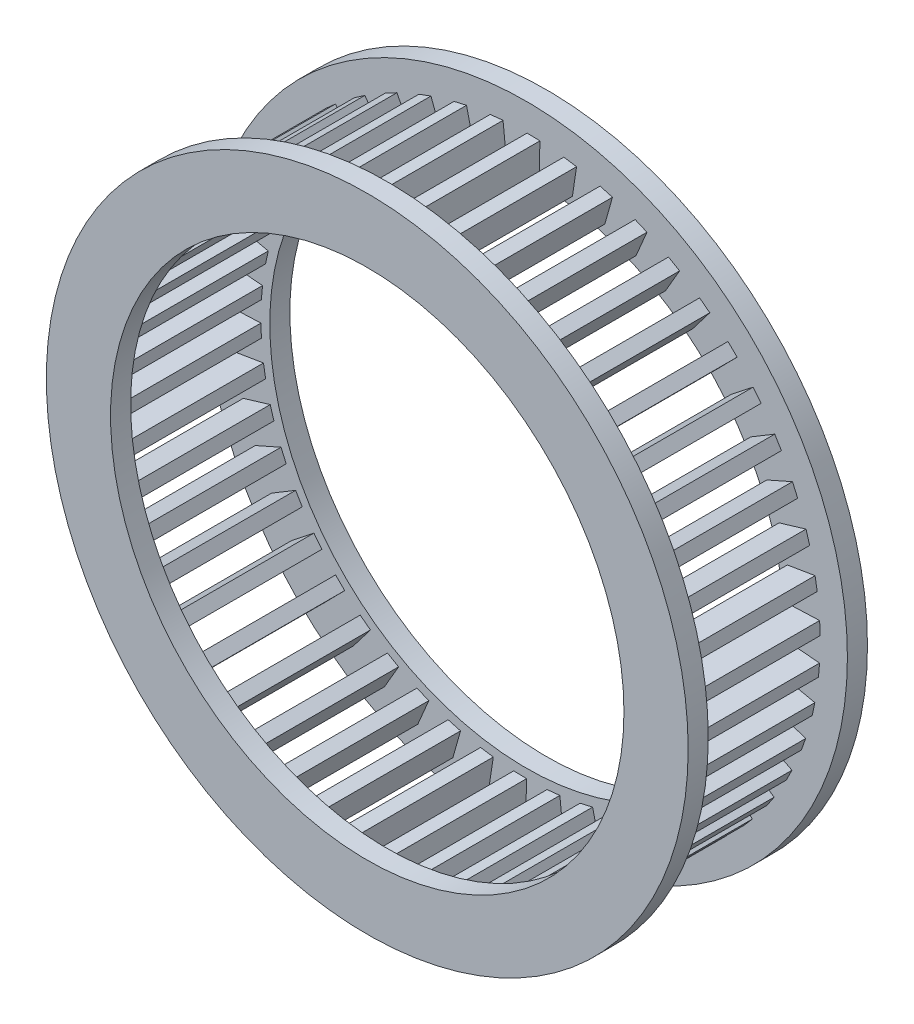
SolidWorks part; units mm, degrees
ref_plane "Спереди" through (0, 0, 0) normal (0, 0, 1) x (1, 0, 0)
ref_plane "Сверху" through (0, 0, 0) normal (0, 1, 0) x (1, 0, 0)
ref_plane "Справа" through (0, 0, 0) normal (1, 0, 0) x (0, 0, -1)
sketch "Эскиз1" plane through (0, 0, 0) normal (0, 0, 1) x (1, 0, 0)
  line L0 (76.3371, 1.1277) -> (84.4079, 1.4423)
  line L1 (84.4079, 1.4423) -> (84.2641, 5.1318)
  line L2 (84.2641, 5.1318) -> (76.1933, 4.8172)
  line L3 (76.1933, 4.8172) -> (76.3371, 1.1277)
  line L4 (75.5938, 10.6864) -> (83.5615, 12.01)
  line L5 (83.5615, 12.01) -> (82.9564, 15.6524)
  line L6 (82.9564, 15.6524) -> (74.9887, 14.3288)
  line L7 (74.9887, 14.3288) -> (75.5938, 10.6864)
  line L8 (73.6584, 20.0765) -> (81.3974, 22.3884)
  line L9 (81.3974, 22.3884) -> (80.3405, 25.9262)
  line L10 (80.3405, 25.9262) -> (72.6015, 23.6144)
  line L11 (72.6015, 23.6144) -> (73.6584, 20.0765)
  line L12 (70.5613, 29.1501) -> (77.9495, 32.4136)
  line L13 (77.9495, 32.4136) -> (76.4576, 35.7911)
  line L14 (76.4576, 35.7911) -> (69.0694, 32.5276)
  line L15 (69.0694, 32.5276) -> (70.5613, 29.1501)
  line L16 (66.3514, 37.7639) -> (73.2724, 41.9277)
  line L17 (73.2724, 41.9277) -> (71.3689, 45.0915)
  line L18 (71.3689, 45.0915) -> (64.448, 40.9278)
  line L19 (64.448, 40.9278) -> (66.3514, 37.7639)
  line L20 (61.0951, 45.7821) -> (67.4396, 50.7805)
  line L21 (67.4396, 50.7805) -> (65.1547, 53.6809)
  line L22 (65.1547, 53.6809) -> (58.8102, 48.6825)
  line L23 (58.8102, 48.6825) -> (61.0951, 45.7821)
  line L24 (54.8754, 53.0784) -> (60.5434, 58.8325)
  line L25 (60.5434, 58.8325) -> (57.9129, 61.4236)
  line L26 (57.9129, 61.4236) -> (52.2449, 55.6695)
  line L27 (52.2449, 55.6695) -> (54.8754, 53.0784)
  line L28 (47.7902, 59.5376) -> (52.6923, 65.9567)
  line L29 (52.6923, 65.9567) -> (49.7578, 68.1977)
  line L30 (49.7578, 68.1977) -> (44.8557, 61.7785)
  line L31 (44.8557, 61.7785) -> (47.7902, 59.5376)
  line L32 (39.9513, 65.0578) -> (44.0102, 72.0407)
  line L33 (44.0102, 72.0407) -> (40.818, 73.8963)
  line L34 (40.818, 73.8963) -> (36.7591, 66.9133)
  line L35 (36.7591, 66.9133) -> (39.9513, 65.0578)
  line L36 (31.4824, 69.552) -> (34.6341, 76.9886)
  line L37 (34.6341, 76.9886) -> (31.2345, 78.4294)
  line L38 (31.2345, 78.4294) -> (28.0828, 70.9928)
  line L39 (28.0828, 70.9928) -> (31.4824, 69.552)
  line L40 (22.5169, 72.9494) -> (24.7118, 80.7223)
  line L41 (24.7118, 80.7223) -> (21.1584, 81.7257)
  line L42 (21.1584, 81.7257) -> (18.9636, 73.9527)
  line L43 (18.9636, 73.9527) -> (22.5169, 72.9494)
  line L44 (13.1964, 75.1962) -> (14.3997, 83.183)
  line L45 (14.3997, 83.183) -> (10.7486, 83.7331)
  line L46 (10.7486, 83.7331) -> (9.5453, 75.7463)
  line L47 (9.5453, 75.7463) -> (13.1964, 75.1962)
  line L48 (3.6678, 76.2572) -> (3.8606, 84.3319)
  line L49 (3.8606, 84.3319) -> (0.1693, 84.42)
  line L50 (0.1693, 84.42) -> (-0.0235, 76.3454)
  line L51 (-0.0235, 76.3454) -> (3.6678, 76.2572)
  line L52 (-5.9187, 76.1156) -> (-6.7394, 84.1507)
  line L53 (-6.7394, 84.1507) -> (-10.4126, 83.7756)
  line L54 (-10.4126, 83.7756) -> (-9.5919, 75.7404)
  line L55 (-9.5919, 75.7404) -> (-5.9187, 76.1156)
  line L56 (-15.4119, 74.7736) -> (-17.2332, 82.6425)
  line L57 (-17.2332, 82.6425) -> (-20.8304, 81.8099)
  line L58 (-20.8304, 81.8099) -> (-19.0091, 73.941)
  line L59 (-19.0091, 73.941) -> (-15.4119, 74.7736)
  line L60 (-24.662, 72.2524) -> (-27.4552, 79.831)
  line L61 (-27.4552, 79.831) -> (-30.9196, 78.5541)
  line L62 (-30.9196, 78.5541) -> (-28.1265, 70.9755)
  line L63 (-28.1265, 70.9755) -> (-24.662, 72.2524)
  line L64 (-33.5231, 68.5917) -> (-37.2441, 75.7604)
  line L65 (-37.2441, 75.7604) -> (-40.5213, 74.0594)
  line L66 (-40.5213, 74.0594) -> (-36.8003, 66.8907)
  line L67 (-36.8003, 66.8907) -> (-33.5231, 68.5917)
  line L68 (-41.8556, 63.8493) -> (-46.4458, 70.4951)
  line L69 (-46.4458, 70.4951) -> (-49.4839, 68.3968)
  line L70 (-49.4839, 68.3968) -> (-44.8937, 61.7509)
  line L71 (-44.8937, 61.7509) -> (-41.8556, 63.8493)
  line L72 (-49.528, 58.0999) -> (-54.9149, 64.118)
  line L73 (-54.9149, 64.118) -> (-57.666, 61.6555)
  line L74 (-57.666, 61.6555) -> (-52.2792, 55.6373)
  line L75 (-52.2792, 55.6373) -> (-49.528, 58.0999)
  line L76 (-56.4193, 51.4343) -> (-62.518, 56.7298)
  line L77 (-62.518, 56.7298) -> (-64.9388, 53.9418)
  line L78 (-64.9388, 53.9418) -> (-58.8401, 48.6463)
  line L79 (-58.8401, 48.6463) -> (-56.4193, 51.4343)
  line L80 (-62.4208, 43.9575) -> (-69.1352, 48.4469)
  line L81 (-69.1352, 48.4469) -> (-71.1875, 45.3775)
  line L82 (-71.1875, 45.3775) -> (-64.4731, 40.8881)
  line L83 (-64.4731, 40.8881) -> (-62.4208, 43.9575)
  line L84 (-67.438, 35.7874) -> (-74.662, 39.3999)
  line L85 (-74.662, 39.3999) -> (-76.3134, 36.0975)
  line L86 (-76.3134, 36.0975) -> (-69.0894, 32.485)
  line L87 (-69.0894, 32.485) -> (-67.438, 35.7874)
  line L88 (-71.3916, 27.053) -> (-79.0114, 29.7316)
  line L89 (-79.0114, 29.7316) -> (-80.2359, 26.2483)
  line L90 (-80.2359, 26.2483) -> (-72.6161, 23.5697)
  line L91 (-72.6161, 23.5697) -> (-71.3916, 27.053)
  line L92 (-74.2193, 17.892) -> (-82.1147, 19.5944)
  line L93 (-82.1147, 19.5944) -> (-82.893, 15.9851)
  line L94 (-82.893, 15.9851) -> (-74.9975, 14.2826)
  line L95 (-74.9975, 14.2826) -> (-74.2193, 17.892)
  line L96 (-75.8765, 8.4487) -> (-83.9231, 9.1482)
  line L97 (-83.9231, 9.1482) -> (-84.2428, 5.4698)
  line L98 (-84.2428, 5.4698) -> (-76.1962, 4.7703)
  line L99 (-76.1962, 4.7703) -> (-75.8765, 8.4487)
  line L100 (-76.3371, -1.1277) -> (-84.4079, -1.4423)
  line L101 (-84.4079, -1.4423) -> (-84.2641, -5.1318)
  line L102 (-84.2641, -5.1318) -> (-76.1933, -4.8172)
  line L103 (-76.1933, -4.8172) -> (-76.3371, -1.1277)
  line L104 (-75.5938, -10.6864) -> (-83.5615, -12.01)
  line L105 (-83.5615, -12.01) -> (-82.9564, -15.6524)
  line L106 (-82.9564, -15.6524) -> (-74.9887, -14.3288)
  line L107 (-74.9887, -14.3288) -> (-75.5938, -10.6864)
  line L108 (-73.6584, -20.0765) -> (-81.3974, -22.3884)
  line L109 (-81.3974, -22.3884) -> (-80.3405, -25.9262)
  line L110 (-80.3405, -25.9262) -> (-72.6015, -23.6144)
  line L111 (-72.6015, -23.6144) -> (-73.6584, -20.0765)
  line L112 (-70.5613, -29.1501) -> (-77.9495, -32.4136)
  line L113 (-77.9495, -32.4136) -> (-76.4576, -35.7911)
  line L114 (-76.4576, -35.7911) -> (-69.0694, -32.5276)
  line L115 (-69.0694, -32.5276) -> (-70.5613, -29.1501)
  line L116 (-66.3514, -37.7639) -> (-73.2724, -41.9277)
  line L117 (-73.2724, -41.9277) -> (-71.3689, -45.0915)
  line L118 (-71.3689, -45.0915) -> (-64.448, -40.9278)
  line L119 (-64.448, -40.9278) -> (-66.3514, -37.7639)
  line L120 (-61.0951, -45.7821) -> (-67.4396, -50.7805)
  line L121 (-67.4396, -50.7805) -> (-65.1547, -53.6809)
  line L122 (-65.1547, -53.6809) -> (-58.8102, -48.6825)
  line L123 (-58.8102, -48.6825) -> (-61.0951, -45.7821)
  line L124 (-54.8754, -53.0784) -> (-60.5434, -58.8325)
  line L125 (-60.5434, -58.8325) -> (-57.9129, -61.4236)
  line L126 (-57.9129, -61.4236) -> (-52.2449, -55.6695)
  line L127 (-52.2449, -55.6695) -> (-54.8754, -53.0784)
  line L128 (-47.7902, -59.5376) -> (-52.6923, -65.9567)
  line L129 (-52.6923, -65.9567) -> (-49.7578, -68.1977)
  line L130 (-49.7578, -68.1977) -> (-44.8557, -61.7785)
  line L131 (-44.8557, -61.7785) -> (-47.7902, -59.5376)
  line L132 (-39.9513, -65.0578) -> (-44.0102, -72.0407)
  line L133 (-44.0102, -72.0407) -> (-40.818, -73.8963)
  line L134 (-40.818, -73.8963) -> (-36.7591, -66.9133)
  line L135 (-36.7591, -66.9133) -> (-39.9513, -65.0578)
  line L136 (-31.4824, -69.552) -> (-34.6341, -76.9886)
  line L137 (-34.6341, -76.9886) -> (-31.2345, -78.4294)
  line L138 (-31.2345, -78.4294) -> (-28.0828, -70.9928)
  line L139 (-28.0828, -70.9928) -> (-31.4824, -69.552)
  line L140 (-22.5169, -72.9494) -> (-24.7118, -80.7223)
  line L141 (-24.7118, -80.7223) -> (-21.1584, -81.7257)
  line L142 (-21.1584, -81.7257) -> (-18.9636, -73.9527)
  line L143 (-18.9636, -73.9527) -> (-22.5169, -72.9494)
  line L144 (-13.1964, -75.1962) -> (-14.3997, -83.183)
  line L145 (-14.3997, -83.183) -> (-10.7486, -83.7331)
  line L146 (-10.7486, -83.7331) -> (-9.5453, -75.7463)
  line L147 (-9.5453, -75.7463) -> (-13.1964, -75.1962)
  line L148 (-3.6678, -76.2572) -> (-3.8606, -84.3319)
  line L149 (-3.8606, -84.3319) -> (-0.1693, -84.42)
  line L150 (-0.1693, -84.42) -> (0.0235, -76.3454)
  line L151 (0.0235, -76.3454) -> (-3.6678, -76.2572)
  line L152 (5.9187, -76.1156) -> (6.7394, -84.1507)
  line L153 (6.7394, -84.1507) -> (10.4126, -83.7756)
  line L154 (10.4126, -83.7756) -> (9.5919, -75.7404)
  line L155 (9.5919, -75.7404) -> (5.9187, -76.1156)
  line L156 (15.4119, -74.7736) -> (17.2332, -82.6425)
  line L157 (17.2332, -82.6425) -> (20.8304, -81.8099)
  line L158 (20.8304, -81.8099) -> (19.0091, -73.941)
  line L159 (19.0091, -73.941) -> (15.4119, -74.7736)
  line L160 (24.662, -72.2524) -> (27.4552, -79.831)
  line L161 (27.4552, -79.831) -> (30.9196, -78.5541)
  line L162 (30.9196, -78.5541) -> (28.1265, -70.9755)
  line L163 (28.1265, -70.9755) -> (24.662, -72.2524)
  line L164 (33.5231, -68.5917) -> (37.2441, -75.7604)
  line L165 (37.2441, -75.7604) -> (40.5213, -74.0594)
  line L166 (40.5213, -74.0594) -> (36.8003, -66.8907)
  line L167 (36.8003, -66.8907) -> (33.5231, -68.5917)
  line L168 (41.8556, -63.8493) -> (46.4458, -70.4951)
  line L169 (46.4458, -70.4951) -> (49.4839, -68.3968)
  line L170 (49.4839, -68.3968) -> (44.8937, -61.7509)
  line L171 (44.8937, -61.7509) -> (41.8556, -63.8493)
  line L172 (49.528, -58.0999) -> (54.9149, -64.118)
  line L173 (54.9149, -64.118) -> (57.666, -61.6555)
  line L174 (57.666, -61.6555) -> (52.2792, -55.6373)
  line L175 (52.2792, -55.6373) -> (49.528, -58.0999)
  line L176 (56.4193, -51.4343) -> (62.518, -56.7298)
  line L177 (62.518, -56.7298) -> (64.9388, -53.9418)
  line L178 (64.9388, -53.9418) -> (58.8401, -48.6463)
  line L179 (58.8401, -48.6463) -> (56.4193, -51.4343)
  line L180 (62.4208, -43.9575) -> (69.1352, -48.4469)
  line L181 (69.1352, -48.4469) -> (71.1875, -45.3775)
  line L182 (71.1875, -45.3775) -> (64.4731, -40.8881)
  line L183 (64.4731, -40.8881) -> (62.4208, -43.9575)
  line L184 (67.438, -35.7874) -> (74.662, -39.3999)
  line L185 (74.662, -39.3999) -> (76.3134, -36.0975)
  line L186 (76.3134, -36.0975) -> (69.0894, -32.485)
  line L187 (69.0894, -32.485) -> (67.438, -35.7874)
  line L188 (71.3916, -27.053) -> (79.0114, -29.7316)
  line L189 (79.0114, -29.7316) -> (80.2359, -26.2483)
  line L190 (80.2359, -26.2483) -> (72.6161, -23.5697)
  line L191 (72.6161, -23.5697) -> (71.3916, -27.053)
  line L192 (74.2193, -17.892) -> (82.1147, -19.5944)
  line L193 (82.1147, -19.5944) -> (82.893, -15.9851)
  line L194 (82.893, -15.9851) -> (74.9975, -14.2826)
  line L195 (74.9975, -14.2826) -> (74.2193, -17.892)
  line L196 (75.8765, -8.4487) -> (83.9231, -9.1482)
  line L197 (83.9231, -9.1482) -> (84.2428, -5.4698)
  line L198 (84.2428, -5.4698) -> (76.1962, -4.7703)
  line L199 (76.1962, -4.7703) -> (75.8765, -8.4487)
extrude "Cage_50_bars" add sketch "Эскиз1" along normal blind 40.2 from offset 20.1 separate body
sketch "Эскиз2" plane through (0, 0, 0) normal (0, 0, 1) x (1, 0, 0)
  circle A0 centre (0, 0) radius 92.2462
  circle A1 centre (0, 0) radius 73.7846
extrude "Cage_ring_right" add sketch "Эскиз2" along normal blind 5.7692 from offset 20
sketch "Эскиз3" plane through (0, 0, 0) normal (0, 0, 1) x (1, 0, 0)
  circle A0 centre (0, 0) radius 92.2462
  circle A1 centre (0, 0) radius 73.7846
extrude "Cage_ring_left" add sketch "Эскиз3" along normal blind 5.7692 from offset 25.7692
